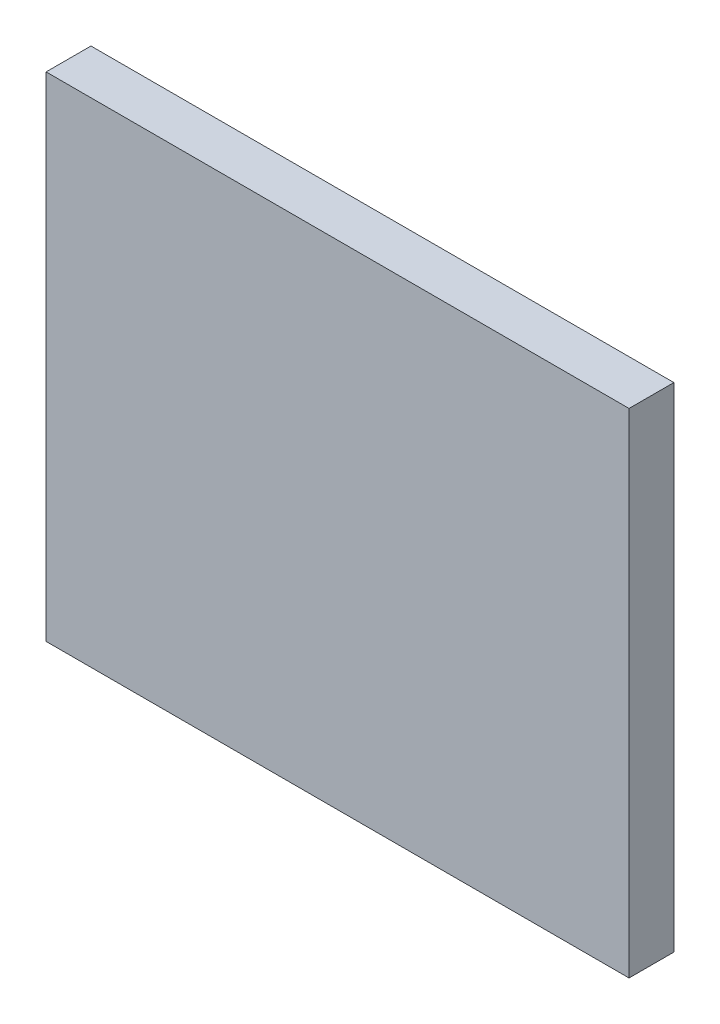
SolidWorks part; units mm, degrees
ref_plane "Front Plane" through (0, 0, 0) normal (0, 0, 1) x (1, 0, 0)
ref_plane "Top Plane" through (0, 0, 0) normal (0, 1, 0) x (1, 0, 0)
ref_plane "Right Plane" through (0, 0, 0) normal (1, 0, 0) x (0, 0, -1)
sketch "Sketch1" plane through (0, 0, 0) normal (0, 0, 1) x (1, 0, 0)
  line L1 (0, 0) -> (330.2, 0)
  line L2 (0, 0) -> (0, 279.4)
  line L3 (0, 279.4) -> (330.2, 279.4)
  line L4 (330.2, 0) -> (330.2, 279.4)
  dimension "D1" = 330.2
  dimension "D2" = 279.4
extrude "Boss-Extrude1" add sketch "Sketch1" along normal blind 25.4
